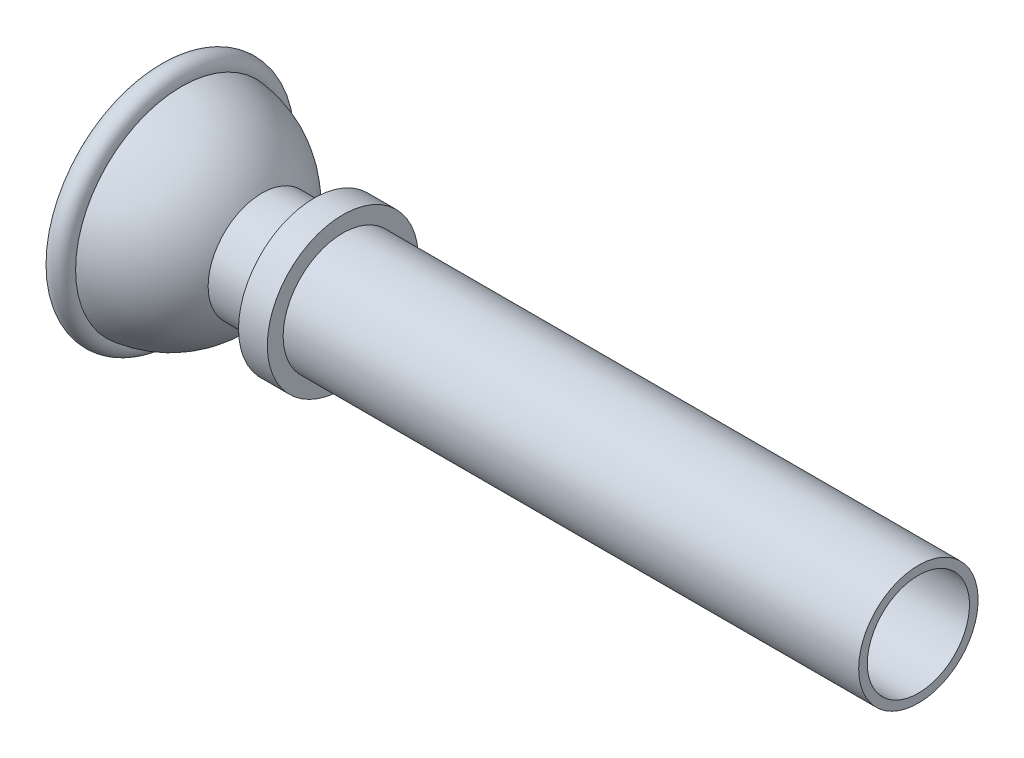
SolidWorks part; units mm, degrees
material "Brass"
ref_plane "Front Plane" through (0, 0, 0) normal (0, 0, 1) x (1, 0, 0)
ref_plane "Top Plane" through (0, 0, 0) normal (0, 1, 0) x (1, 0, 0)
ref_plane "Right Plane" through (0, 0, 0) normal (1, 0, 0) x (0, 0, -1)
sketch "Sketch1" plane through (0, 0, 0) normal (0, 0, 1) x (1, 0, 0)
  line L0 (117.559, 6.4961) -> (15.959, 6.4961)
  line L1 (15.959, 6.4961) -> (15.959, 3.8291)
  line L2 (15.959, 3.8291) -> (10.879, 3.8291)
  line L3 (117.559, 6.4961) -> (117.559, 8.0201)
  line L4 (117.559, 8.0201) -> (15.959, 8.0201)
  line L5 (15.959, 8.0201) -> (15.959, 10.8141)
  line L6 (15.959, 10.8141) -> (10.879, 10.8141)
  line L7 (10.879, 10.8141) -> (10.879, 6.9968)
  line L8 (10.879, 6.9968) -> (1.696, 6.9968)
  line L9 (-17.5997, -2.5209) -> (37.7891, -2.5209) construction
  line L11 (-14.521, 6.9968) -> (-14.521, 14.4971) construction
  line L12 (10.879, 6.9968) -> (10.879, 3.8291) construction
  line L13 (10.879, 3.8291) -> (1.2679, 3.8291)
  line L14 (-14.521, -2.5209) -> (-14.521, 6.9968) construction
  arc A0 (-12.5199, 16.176) -> (-14.521, 14.4971) centre (-14.521, 16.5291) ccw
  arc A1 (1.2679, 3.8291) -> (-14.521, 14.4971) centre (-14.521, -2.5209) ccw
  arc A2 (1.696, 6.9968) -> (-12.5199, 16.176) centre (-14.521, -2.5209) ccw
  dimension "D8" = 4.064
  dimension "D1" = 10.541
  dimension "D2" = 9.017
  dimension "D3" = 25.4
  dimension "D4" = 5.08
  dimension "D5" = 132.08
  dimension "D6" = 13.335
  dimension "D7" = 6.35
  dimension "D9" = 19.05
revolve "Revolve1" add sketch "Sketch1" angle 360 about L9
